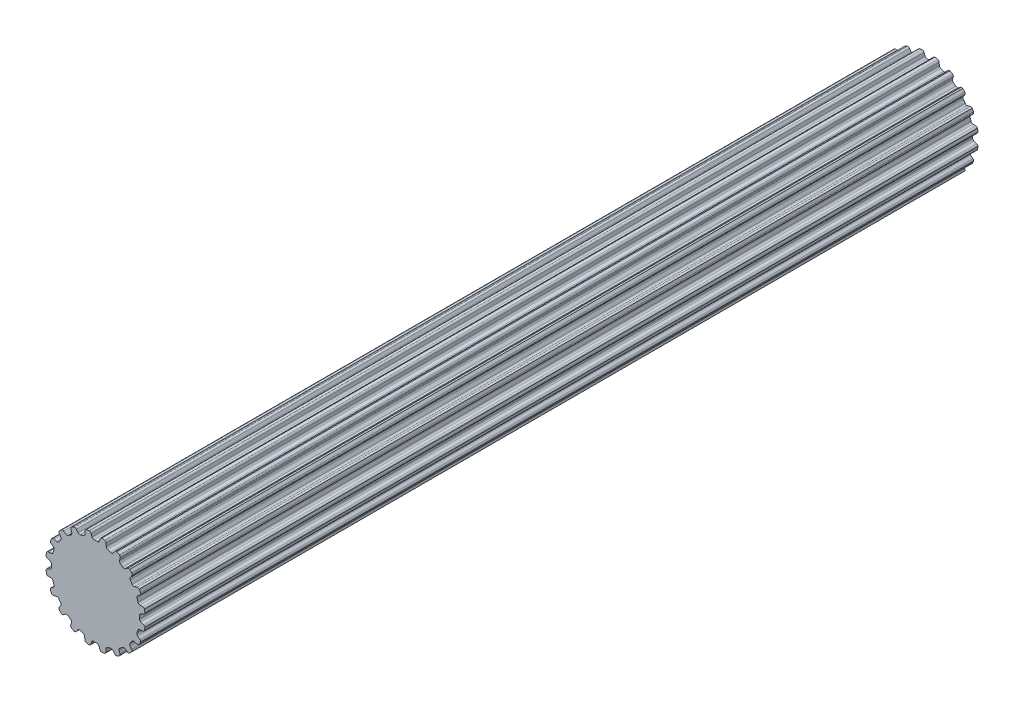
SolidWorks part; units mm, degrees
ref_plane "Front Plane" through (0, 0, 0) normal (0, 0, 1) x (1, 0, 0)
ref_plane "Top Plane" through (0, 0, 0) normal (0, 1, 0) x (1, 0, 0)
ref_plane "Right Plane" through (0, 0, 0) normal (1, 0, 0) x (0, 0, -1)
sketch "Sketch1" plane through (0, 0, 0) normal (0, 0, 1) x (1, 0, 0)
  line L0 (-0.1069, 2.9699) -> (0.1069, 2.9699)
  line L1 (0.3159, 3.2375) -> (0.2537, 3.0575)
  line L2 (-0.2964, 3.2367) -> (-0.2318, 3.0575)
  line L3 (-0.2964, 3.2367) -> (0.3159, 3.2375) construction
  line L4 (0, 3.3252) -> (0, 0) construction
  line L5 (-0.2318, 3.0575) -> (0.2537, 3.0575) construction
  line L6 (-0.4281, 3.3241) -> (0.4281, 3.3263) construction
  line L7 (0.7183, 3.1698) -> (0.7244, 2.9795)
  line L8 (0.816, 2.8576) -> (1.0195, 2.7915)
  line L9 (1.3009, 2.9815) -> (1.1862, 2.8295)
  line L10 (1.6627, 2.7927) -> (1.6097, 2.6099)
  line L11 (1.6591, 2.4655) -> (1.8322, 2.3398)
  line L12 (2.1585, 2.4335) -> (2.0025, 2.3245)
  line L13 (2.4443, 2.1423) -> (2.3374, 1.9847)
  line L14 (2.3398, 1.8322) -> (2.4655, 1.6591)
  line L15 (2.8049, 1.6474) -> (2.6228, 1.5919)
  line L16 (2.9866, 1.2821) -> (2.8363, 1.1653)
  line L17 (2.7915, 1.0195) -> (2.8576, 0.816)
  line L18 (3.1767, 0.7) -> (2.9863, 0.7035)
  line L19 (3.2367, 0.2964) -> (3.0575, 0.2318)
  line L20 (2.9699, 0.1069) -> (2.9699, -0.1069)
  line L21 (3.2375, -0.3159) -> (3.0575, -0.2537)
  line L22 (3.1698, -0.7183) -> (2.9795, -0.7244)
  line L23 (2.8576, -0.816) -> (2.7915, -1.0195)
  line L24 (2.9815, -1.3009) -> (2.8295, -1.1862)
  line L25 (2.7927, -1.6627) -> (2.6099, -1.6097)
  line L26 (2.4655, -1.6591) -> (2.3398, -1.8322)
  line L27 (2.4335, -2.1585) -> (2.3245, -2.0025)
  line L28 (2.1423, -2.4443) -> (1.9847, -2.3374)
  line L29 (1.8322, -2.3398) -> (1.6591, -2.4655)
  line L30 (1.6474, -2.8049) -> (1.5919, -2.6228)
  line L31 (1.2821, -2.9866) -> (1.1653, -2.8363)
  line L32 (1.0195, -2.7915) -> (0.816, -2.8576)
  line L33 (0.7, -3.1767) -> (0.7035, -2.9863)
  line L34 (0.2964, -3.2367) -> (0.2318, -3.0575)
  line L35 (0.1069, -2.9699) -> (-0.1069, -2.9699)
  line L36 (-0.3159, -3.2375) -> (-0.2537, -3.0575)
  line L37 (-0.7183, -3.1698) -> (-0.7244, -2.9795)
  line L38 (-0.816, -2.8576) -> (-1.0195, -2.7915)
  line L39 (-1.3009, -2.9815) -> (-1.1862, -2.8295)
  line L40 (-1.6627, -2.7927) -> (-1.6097, -2.6099)
  line L41 (-1.6591, -2.4655) -> (-1.8322, -2.3398)
  line L42 (-2.1585, -2.4335) -> (-2.0025, -2.3245)
  line L43 (-2.4443, -2.1423) -> (-2.3374, -1.9847)
  line L44 (-2.3398, -1.8322) -> (-2.4655, -1.6591)
  line L45 (-2.8049, -1.6474) -> (-2.6228, -1.5919)
  line L46 (-2.9866, -1.2821) -> (-2.8363, -1.1653)
  line L47 (-2.7915, -1.0195) -> (-2.8576, -0.816)
  line L48 (-3.1767, -0.7) -> (-2.9863, -0.7035)
  line L49 (-3.2367, -0.2964) -> (-3.0575, -0.2318)
  line L50 (-2.9699, -0.1069) -> (-2.9699, 0.1069)
  line L51 (-3.2375, 0.3159) -> (-3.0575, 0.2537)
  line L52 (-3.1698, 0.7183) -> (-2.9795, 0.7244)
  line L53 (-2.8576, 0.816) -> (-2.7915, 1.0195)
  line L54 (-2.9815, 1.3009) -> (-2.8295, 1.1862)
  line L55 (-2.7927, 1.6627) -> (-2.6099, 1.6097)
  line L56 (-2.4655, 1.6591) -> (-2.3398, 1.8322)
  line L57 (-2.4335, 2.1585) -> (-2.3245, 2.0025)
  line L58 (-2.1423, 2.4443) -> (-1.9847, 2.3374)
  line L59 (-1.8322, 2.3398) -> (-1.6591, 2.4655)
  line L60 (-1.6474, 2.8049) -> (-1.5919, 2.6228)
  line L61 (-1.2821, 2.9866) -> (-1.1653, 2.8363)
  line L62 (-1.0195, 2.7915) -> (-0.816, 2.8576)
  line L63 (-0.7, 3.1767) -> (-0.7035, 2.9863)
  line L64 (0.4281, 3.3263) -> (0.62, 3.2938)
  line L65 (1.4351, 3.0312) -> (1.6075, 2.9409)
  line L66 (2.3015, 2.4394) -> (2.4376, 2.3003)
  line L67 (2.9427, 1.6088) -> (3.0291, 1.4344)
  line L68 (3.2958, 0.6207) -> (3.3241, 0.4281)
  line L69 (3.3263, -0.4281) -> (3.2938, -0.62)
  line L70 (3.0312, -1.4351) -> (2.9409, -1.6075)
  line L71 (2.4394, -2.3015) -> (2.3003, -2.4376)
  line L72 (1.6088, -2.9427) -> (1.4344, -3.0291)
  line L73 (0.6207, -3.2958) -> (0.4281, -3.3241)
  line L74 (-0.4281, -3.3263) -> (-0.62, -3.2938)
  line L75 (-1.4351, -3.0312) -> (-1.6075, -2.9409)
  line L76 (-2.3015, -2.4394) -> (-2.4376, -2.3003)
  line L77 (-2.9427, -1.6088) -> (-3.0291, -1.4344)
  line L78 (-3.2958, -0.6207) -> (-3.3241, -0.4281)
  line L79 (-3.3263, 0.4281) -> (-3.2938, 0.62)
  line L80 (-3.0312, 1.4351) -> (-2.9409, 1.6075)
  line L81 (-2.4394, 2.3015) -> (-2.3003, 2.4376)
  line L82 (-1.6088, 2.9427) -> (-1.4344, 3.0291)
  line L83 (-0.6207, 3.2958) -> (-0.4281, 3.3241)
  arc A0 (0.2537, 3.0575) -> (0.1069, 2.9699) centre (0.1283, 3.1009) cw
  arc A1 (-0.2318, 3.0575) -> (-0.1069, 2.9699) centre (-0.1069, 3.1026) ccw
  arc A2 (0.62, 3.2938) -> (0.7183, 3.1698) centre (0.5856, 3.1656) cw
  arc A3 (0.7244, 2.9795) -> (0.816, 2.8576) centre (0.857, 2.9838) ccw
  arc A4 (-0.4281, 3.3241) -> (-0.2964, 3.2367) centre (-0.4213, 3.1916) cw
  arc A5 (0.4281, 3.3263) -> (0.3159, 3.2375) centre (0.4413, 3.1942) ccw
  arc A6 (1.1862, 2.8295) -> (1.0195, 2.7915) centre (1.0802, 2.9095) cw
  arc A7 (1.4351, 3.0312) -> (1.3009, 2.9815) centre (1.4068, 2.9015) ccw
  arc A8 (1.6075, 2.9409) -> (1.6627, 2.7927) centre (1.5352, 2.8297) cw
  arc A9 (1.6097, 2.6099) -> (1.6591, 2.4655) centre (1.7371, 2.5729) ccw
  arc A10 (2.0025, 2.3245) -> (1.8322, 2.3398) centre (1.9264, 2.4332) cw
  arc A11 (2.3015, 2.4394) -> (2.1585, 2.4335) centre (2.2346, 2.3248) ccw
  arc A12 (2.4376, 2.3003) -> (2.4443, 2.1423) centre (2.3345, 2.2168) cw
  arc A13 (2.3374, 1.9847) -> (2.3398, 1.8322) centre (2.4472, 1.9102) ccw
  arc A14 (2.6228, 1.5919) -> (2.4655, 1.6591) centre (2.5841, 1.7189) cw
  arc A15 (2.9427, 1.6088) -> (2.8049, 1.6474) centre (2.8436, 1.5205) ccw
  arc A16 (3.0291, 1.4344) -> (2.9866, 1.2821) centre (2.9052, 1.3869) cw
  arc A17 (2.8363, 1.1653) -> (2.7915, 1.0195) centre (2.9177, 1.0605) ccw
  arc A18 (2.9863, 0.7035) -> (2.8576, 0.816) centre (2.9887, 0.8362) cw
  arc A19 (3.2958, 0.6207) -> (3.1767, 0.7) centre (3.1743, 0.5673) ccw
  arc A20 (3.3241, 0.4281) -> (3.2367, 0.2964) centre (3.1916, 0.4213) cw
  arc A21 (3.0575, 0.2318) -> (2.9699, 0.1069) centre (3.1026, 0.1069) ccw
  arc A22 (3.0575, -0.2537) -> (2.9699, -0.1069) centre (3.1009, -0.1283) cw
  arc A23 (3.3263, -0.4281) -> (3.2375, -0.3159) centre (3.1942, -0.4413) ccw
  arc A24 (3.2938, -0.62) -> (3.1698, -0.7183) centre (3.1656, -0.5856) cw
  arc A25 (2.9795, -0.7244) -> (2.8576, -0.816) centre (2.9838, -0.857) ccw
  arc A26 (2.8295, -1.1862) -> (2.7915, -1.0195) centre (2.9095, -1.0802) cw
  arc A27 (3.0312, -1.4351) -> (2.9815, -1.3009) centre (2.9015, -1.4068) ccw
  arc A28 (2.9409, -1.6075) -> (2.7927, -1.6627) centre (2.8297, -1.5352) cw
  arc A29 (2.6099, -1.6097) -> (2.4655, -1.6591) centre (2.5729, -1.7371) ccw
  arc A30 (2.3245, -2.0025) -> (2.3398, -1.8322) centre (2.4332, -1.9264) cw
  arc A31 (2.4394, -2.3015) -> (2.4335, -2.1585) centre (2.3248, -2.2346) ccw
  arc A32 (2.3003, -2.4376) -> (2.1423, -2.4443) centre (2.2168, -2.3345) cw
  arc A33 (1.9847, -2.3374) -> (1.8322, -2.3398) centre (1.9102, -2.4472) ccw
  arc A34 (1.5919, -2.6228) -> (1.6591, -2.4655) centre (1.7189, -2.5841) cw
  arc A35 (1.6088, -2.9427) -> (1.6474, -2.8049) centre (1.5205, -2.8436) ccw
  arc A36 (1.4344, -3.0291) -> (1.2821, -2.9866) centre (1.3869, -2.9052) cw
  arc A37 (1.1653, -2.8363) -> (1.0195, -2.7915) centre (1.0605, -2.9177) ccw
  arc A38 (0.7035, -2.9863) -> (0.816, -2.8576) centre (0.8362, -2.9887) cw
  arc A39 (0.6207, -3.2958) -> (0.7, -3.1767) centre (0.5673, -3.1743) ccw
  arc A40 (0.4281, -3.3241) -> (0.2964, -3.2367) centre (0.4213, -3.1916) cw
  arc A41 (0.2318, -3.0575) -> (0.1069, -2.9699) centre (0.1069, -3.1026) ccw
  arc A42 (-0.2537, -3.0575) -> (-0.1069, -2.9699) centre (-0.1283, -3.1009) cw
  arc A43 (-0.4281, -3.3263) -> (-0.3159, -3.2375) centre (-0.4413, -3.1942) ccw
  arc A44 (-0.62, -3.2938) -> (-0.7183, -3.1698) centre (-0.5856, -3.1656) cw
  arc A45 (-0.7244, -2.9795) -> (-0.816, -2.8576) centre (-0.857, -2.9838) ccw
  arc A46 (-1.1862, -2.8295) -> (-1.0195, -2.7915) centre (-1.0802, -2.9095) cw
  arc A47 (-1.4351, -3.0312) -> (-1.3009, -2.9815) centre (-1.4068, -2.9015) ccw
  arc A48 (-1.6075, -2.9409) -> (-1.6627, -2.7927) centre (-1.5352, -2.8297) cw
  arc A49 (-1.6097, -2.6099) -> (-1.6591, -2.4655) centre (-1.7371, -2.5729) ccw
  arc A50 (-2.0025, -2.3245) -> (-1.8322, -2.3398) centre (-1.9264, -2.4332) cw
  arc A51 (-2.3015, -2.4394) -> (-2.1585, -2.4335) centre (-2.2346, -2.3248) ccw
  arc A52 (-2.4376, -2.3003) -> (-2.4443, -2.1423) centre (-2.3345, -2.2168) cw
  arc A53 (-2.3374, -1.9847) -> (-2.3398, -1.8322) centre (-2.4472, -1.9102) ccw
  arc A54 (-2.6228, -1.5919) -> (-2.4655, -1.6591) centre (-2.5841, -1.7189) cw
  arc A55 (-2.9427, -1.6088) -> (-2.8049, -1.6474) centre (-2.8436, -1.5205) ccw
  arc A56 (-3.0291, -1.4344) -> (-2.9866, -1.2821) centre (-2.9052, -1.3869) cw
  arc A57 (-2.8363, -1.1653) -> (-2.7915, -1.0195) centre (-2.9177, -1.0605) ccw
  arc A58 (-2.9863, -0.7035) -> (-2.8576, -0.816) centre (-2.9887, -0.8362) cw
  arc A59 (-3.2958, -0.6207) -> (-3.1767, -0.7) centre (-3.1743, -0.5673) ccw
  arc A60 (-3.3241, -0.4281) -> (-3.2367, -0.2964) centre (-3.1916, -0.4213) cw
  arc A61 (-3.0575, -0.2318) -> (-2.9699, -0.1069) centre (-3.1026, -0.1069) ccw
  arc A62 (-3.0575, 0.2537) -> (-2.9699, 0.1069) centre (-3.1009, 0.1283) cw
  arc A63 (-3.3263, 0.4281) -> (-3.2375, 0.3159) centre (-3.1942, 0.4413) ccw
  arc A64 (-3.2938, 0.62) -> (-3.1698, 0.7183) centre (-3.1656, 0.5856) cw
  arc A65 (-2.9795, 0.7244) -> (-2.8576, 0.816) centre (-2.9838, 0.857) ccw
  arc A66 (-2.8295, 1.1862) -> (-2.7915, 1.0195) centre (-2.9095, 1.0802) cw
  arc A67 (-3.0312, 1.4351) -> (-2.9815, 1.3009) centre (-2.9015, 1.4068) ccw
  arc A68 (-2.9409, 1.6075) -> (-2.7927, 1.6627) centre (-2.8297, 1.5352) cw
  arc A69 (-2.6099, 1.6097) -> (-2.4655, 1.6591) centre (-2.5729, 1.7371) ccw
  arc A70 (-2.3245, 2.0025) -> (-2.3398, 1.8322) centre (-2.4332, 1.9264) cw
  arc A71 (-2.4394, 2.3015) -> (-2.4335, 2.1585) centre (-2.3248, 2.2346) ccw
  arc A72 (-2.3003, 2.4376) -> (-2.1423, 2.4443) centre (-2.2168, 2.3345) cw
  arc A73 (-1.9847, 2.3374) -> (-1.8322, 2.3398) centre (-1.9102, 2.4472) ccw
  arc A74 (-1.5919, 2.6228) -> (-1.6591, 2.4655) centre (-1.7189, 2.5841) cw
  arc A75 (-1.6088, 2.9427) -> (-1.6474, 2.8049) centre (-1.5205, 2.8436) ccw
  arc A76 (-1.4344, 3.0291) -> (-1.2821, 2.9866) centre (-1.3869, 2.9052) cw
  arc A77 (-1.1653, 2.8363) -> (-1.0195, 2.7915) centre (-1.0605, 2.9177) ccw
  arc A78 (-0.7035, 2.9863) -> (-0.816, 2.8576) centre (-0.8362, 2.9887) cw
  arc A79 (-0.6207, 3.2958) -> (-0.7, 3.1767) centre (-0.5673, 3.1743) ccw
  point P14 (0, 2.9699)
  point P247 (0, 0)
  dimension "D4" = 0.1327
  dimension "D8" = 20
  dimension "D1" = 2.9699
  dimension "D2" = 0.2139
  dimension "D3" = 0.1904
  dimension "D5" = 0.0877
  dimension "D6" = 0.4855
  dimension "D7" = 0.8563
extrude "Boss-Extrude1" add sketch "Sketch1" along normal mid plane 56.007
sketch "Sketch2" plane through (0, 0, 28.0035) normal (0, 0, 1) x (1, 0, 0)
  circle A0 centre (0, 0) radius 3.3516 construction
sketch "Sketch3" plane through (0, 0, -28.0035) normal (0, 0, -1) x (-1, 0, 0)
  circle A0 centre (0, 0) radius 3.3516 construction
  circle A1 centre (0, 0) radius 3.3516 construction
